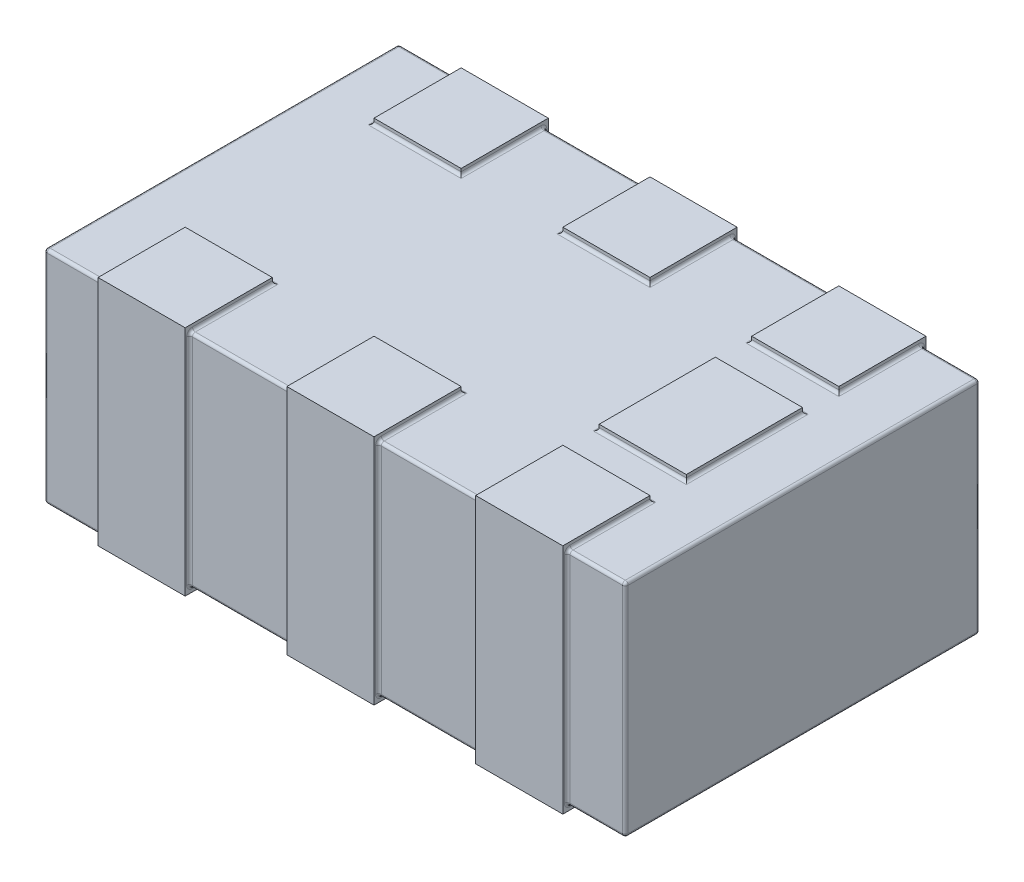
SolidWorks part; units mm, degrees
ref_plane "Спереди" through (0, 0, 0) normal (0, 0, 1) x (1, 0, 0)
ref_plane "Сверху" through (0, 0, 0) normal (0, 1, 0) x (1, 0, 0)
ref_plane "Справа" through (0, 0, 0) normal (1, 0, 0) x (0, 0, -1)
sketch "Эскиз2" plane through (0, 0, 0) normal (0, 1, 0) x (1, 0, 0)
  line L0 (0.8, 0.625) -> (0.8, -0.625) construction
  line L1 (1, -0.625) -> (-1, -0.625) construction
  line L2 (1, -0.625) -> (1, 0.625) construction
  line L3 (1, 0.625) -> (-1, 0.625) construction
  line L4 (-1, -0.625) -> (-1, 0.625) construction
  line L5 (1, -0.625) -> (-1, 0.625) construction
  line L6 (1, 0.625) -> (-1, -0.625) construction
  line L7 (0.15, 0.625) -> (-0.15, 0.625)
  line L8 (0.8, 0.625) -> (0.5, 0.625)
  line L9 (0.8, 0.625) -> (0.8, 0.325)
  line L10 (0.8, 0.325) -> (0.5, 0.325)
  line L11 (0.5, 0.625) -> (0.5, 0.325)
  line L12 (0.15, 0.625) -> (0.15, 0.325)
  line L13 (0.15, 0.325) -> (-0.15, 0.325)
  line L14 (-0.15, 0.625) -> (-0.15, 0.325)
  line L15 (-0.5, 0.625) -> (-0.8, 0.625)
  line L16 (-0.5, 0.625) -> (-0.5, 0.325)
  line L17 (-0.5, 0.325) -> (-0.8, 0.325)
  line L18 (-0.8, 0.625) -> (-0.8, 0.325)
  line L19 (0.8, -0.325) -> (0.5, -0.325)
  line L20 (0.8, -0.325) -> (0.8, -0.625)
  line L21 (0.8, -0.625) -> (0.5, -0.625)
  line L22 (0.5, -0.325) -> (0.5, -0.625)
  line L23 (0.15, -0.325) -> (-0.15, -0.325)
  line L24 (0.15, -0.325) -> (0.15, -0.625)
  line L25 (0.15, -0.625) -> (-0.15, -0.625)
  line L26 (-0.15, -0.325) -> (-0.15, -0.625)
  line L27 (-0.5, -0.325) -> (-0.8, -0.325)
  line L28 (-0.5, -0.325) -> (-0.5, -0.625)
  line L29 (-0.5, -0.625) -> (-0.8, -0.625)
  line L30 (-0.8, -0.325) -> (-0.8, -0.625)
  point P0 (0, 0)
  dimension "D1" = 2
  dimension "D2" = 1.25
  dimension "D3" = 0.2
  dimension "D4" = 0.3
  dimension "D5" = 0.3
  dimension "D6" = 3
  dimension "D7" = 2
extrude "Бобышка-Вытянуть1" add sketch "Эскиз2" along normal blind 0.02
ref_plane "Плоскость1" through (0, 0.02, 0) normal (0, -1, 0) x (1, 0, 0)
sketch "Эскиз3" plane through (0, 0.02, 0) normal (0, -1, 0) x (1, 0, 0)
  line L0 (-0.5, 0.625) -> (-0.5, 0.325) construction
  line L1 (1, 0.61) -> (-1, 0.61)
  line L2 (1, 0.61) -> (1, -0.61)
  line L3 (1, -0.61) -> (-1, -0.61)
  line L4 (-1, 0.61) -> (-1, -0.61)
  line L5 (1, 0.61) -> (-1, -0.61) construction
  line L6 (1, -0.61) -> (-1, 0.61) construction
  line L7 (-0.8, 0.325) -> (-0.5, 0.325)
  line L8 (-0.8, 0.325) -> (-0.8, 0.625)
  line L9 (-0.8, 0.625) -> (-0.5, 0.625)
  line L10 (-0.5, 0.325) -> (-0.5, 0.625)
  line L11 (-0.15, 0.325) -> (0.15, 0.325)
  line L12 (0.15, 0.325) -> (0.15, 0.625)
  line L13 (-0.15, 0.625) -> (0.15, 0.625)
  line L14 (-0.15, 0.325) -> (-0.15, 0.625)
  line L15 (0.5, 0.325) -> (0.8, 0.325)
  line L16 (0.8, 0.325) -> (0.8, 0.625)
  line L17 (0.5, 0.625) -> (0.8, 0.625)
  line L18 (0.5, 0.325) -> (0.5, 0.625)
  line L19 (-0.8, -0.625) -> (-0.5, -0.625)
  line L20 (-0.5, -0.625) -> (-0.5, -0.325)
  line L21 (-0.8, -0.325) -> (-0.5, -0.325)
  line L22 (-0.8, -0.625) -> (-0.8, -0.325)
  line L23 (-0.15, -0.625) -> (0.15, -0.625)
  line L24 (0.15, -0.625) -> (0.15, -0.325)
  line L25 (-0.15, -0.325) -> (0.15, -0.325)
  line L26 (-0.15, -0.625) -> (-0.15, -0.325)
  line L27 (0.5, -0.625) -> (0.8, -0.625)
  line L28 (0.8, -0.625) -> (0.8, -0.325)
  line L29 (0.5, -0.325) -> (0.8, -0.325)
  line L30 (0.5, -0.625) -> (0.5, -0.325)
  point P0 (0, 0)
  dimension "D1" = 1.22
  dimension "D2" = 2
  dimension "D3" = 3
  dimension "D5" = 1.25
  dimension "D4" = 2
extrude "Бобышка-Вытянуть5" add sketch "Эскиз3" against normal blind 0.76 contours L3 L30 L29 L28 L2 L1 L16 L15 L18 L12 L11 L14 L10 L7 L8 L4 L22 L21 L20 L26 L25 L24
sketch "Эскиз4" plane through (0, 0.02, 0) normal (0, -1, 0) x (1, 0, 0)
  line L0 (-0.15, 0.325) -> (-0.15, 0.625)
  line L1 (-0.8, 0.325) -> (-0.5, 0.325)
  line L2 (-0.8, 0.325) -> (-0.8, 0.625)
  line L3 (-0.8, 0.625) -> (-0.5, 0.625)
  line L4 (-0.5, 0.325) -> (-0.5, 0.625)
  line L5 (-0.15, 0.325) -> (0.15, 0.325)
  line L6 (0.15, 0.325) -> (0.15, 0.625)
  line L7 (-0.15, 0.625) -> (0.15, 0.625)
  line L8 (0.5, 0.325) -> (0.5, 0.625)
  line L9 (0.5, 0.325) -> (0.8, 0.325)
  line L10 (0.8, 0.325) -> (0.8, 0.625)
  line L11 (0.5, 0.625) -> (0.8, 0.625)
  line L12 (-0.8, -0.625) -> (-0.8, -0.325)
  line L13 (-0.8, -0.625) -> (-0.5, -0.625)
  line L14 (-0.5, -0.625) -> (-0.5, -0.325)
  line L15 (-0.8, -0.325) -> (-0.5, -0.325)
  line L16 (-0.15, -0.625) -> (-0.15, -0.325)
  line L17 (-0.15, -0.625) -> (0.15, -0.625)
  line L18 (0.15, -0.625) -> (0.15, -0.325)
  line L19 (-0.15, -0.325) -> (0.15, -0.325)
  line L20 (0.5, -0.625) -> (0.5, -0.325)
  line L21 (0.5, -0.625) -> (0.8, -0.625)
  line L22 (0.8, -0.625) -> (0.8, -0.325)
  line L23 (0.5, -0.325) -> (0.8, -0.325)
  dimension "D1" = 3
  dimension "D2" = 2
extrude "Бобышка-Вытянуть6" add sketch "Эскиз4" against normal blind 0.78
sketch "Эскиз5" plane through (0, 0.78, 0) normal (0, 1, 0) x (1, 0, 0)
  line L0 (0.8, 0.325) -> (0.8, -0.325) construction
  line L1 (0.8, 0.2) -> (0.5, 0.2)
  line L2 (0.8, 0.2) -> (0.8, -0.2)
  line L3 (0.8, -0.2) -> (0.5, -0.2)
  line L4 (0.5, 0.2) -> (0.5, -0.2)
  dimension "D1" = 0.3
  dimension "D2" = 0.4
extrude "Бобышка-Вытянуть7" add sketch "Эскиз5" along normal blind 0.02
fillet "Скругление1" radius 0.01 76 edges at (0.5, 0.4, -0.61) (0.15, 0.4, -0.61) (-0.15, 0.4, -0.61) (-0.5, 0.4, -0.61) (-0.8, 0.4, -0.61) (-1, 0.4, -0.61) (-1, 0.4, 0.61) (-0.8, 0.4, 0.61) (-0.5, 0.4, 0.61) (-0.15, 0.4, 0.61) (0.15, 0.4, 0.61) (0.5, 0.4, 0.61) (0.8, 0.4, 0.61) (1, 0.4, 0.61) (1, 0.4, -0.61) (0.8, 0.4, -0.61) (-0.15, 0.02, -0.4675) (-0.325, 0.02, -0.61) (-0.5, 0.02, -0.4675) (-0.65, 0.02, -0.325) (-0.8, 0.02, -0.4675) (-0.9, 0.02, -0.61) (-1, 0.02, 0) (-0.9, 0.02, 0.61) (-0.8, 0.02, 0.4675) (-0.65, 0.02, 0.325) (-0.5, 0.02, 0.4675) (-0.325, 0.02, 0.61) (-0.15, 0.02, 0.4675) (0, 0.02, 0.325) (0.15, 0.02, 0.4675) (0.325, 0.02, 0.61) (0.5, 0.02, 0.4675) (0.65, 0.02, 0.325) (0.8, 0.02, 0.4675) (0.9, 0.02, 0.61) (1, 0.02, 0) (0.9, 0.02, -0.61) (0.8, 0.78, -0.4675) (0.8, 0.02, -0.4675) (0.65, 0.02, -0.325) (0.65, 0.78, -0.325) (0.5, 0.78, -0.4675) (0.5, 0.02, -0.4675) (0.325, 0.02, -0.61) (0.15, 0.02, -0.4675) (0, 0.02, -0.325) (0.65, 0.78, -0.2) (0.5, 0.78, 0) (0.65, 0.78, 0.2) (0.8, 0.78, 0) (0.9, 0.78, -0.61) (1, 0.78, 0) (0.9, 0.78, 0.61) (0.8, 0.78, 0.4675) (0.65, 0.78, 0.325) (0.5, 0.78, 0.4675) (0.325, 0.78, 0.61) (0.15, 0.78, 0.4675) (0, 0.78, 0.325) (-0.15, 0.78, 0.4675) (-0.325, 0.78, 0.61) (-0.5, 0.78, 0.4675) (-0.65, 0.78, 0.325) (-0.8, 0.78, 0.4675) (-0.9, 0.78, 0.61) (-1, 0.78, 0) (-0.9, 0.78, -0.61) (-0.8, 0.78, -0.4675) (-0.65, 0.78, -0.325) (-0.5, 0.78, -0.4675) (-0.325, 0.78, -0.61) (-0.15, 0.78, -0.4675) (0, 0.78, -0.325) (0.15, 0.78, -0.4675) (0.325, 0.78, -0.61)
